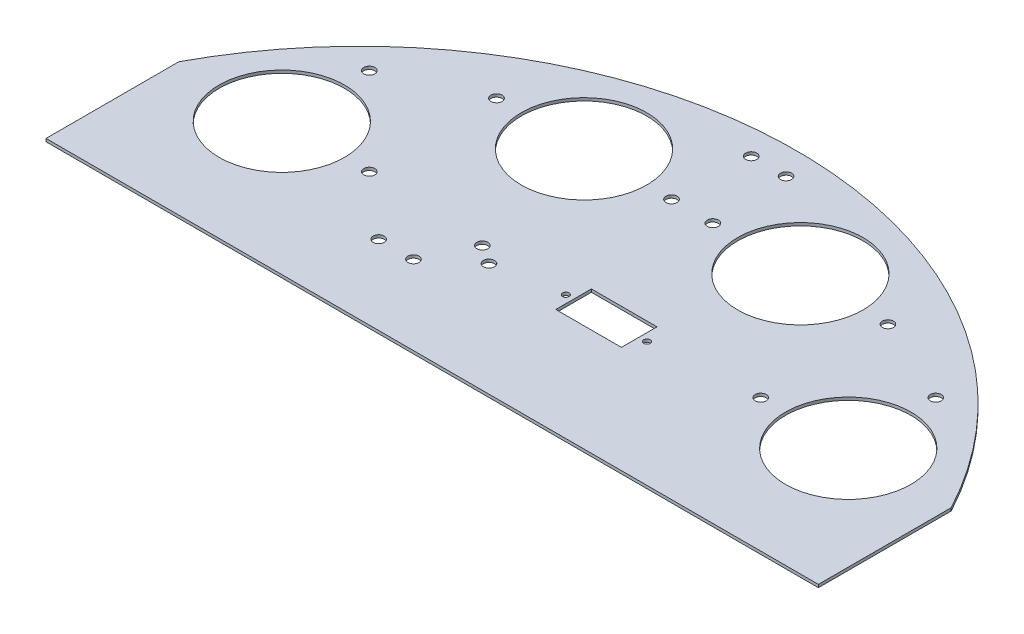
SolidWorks part; units mm, degrees
material "1060 Alloy"
ref_plane "Front Plane" through (0, 0, 0) normal (0, 0, 1) x (1, 0, 0)
ref_plane "Top Plane" through (0, 0, 0) normal (0, 1, 0) x (1, 0, 0)
ref_plane "Right Plane" through (0, 0, 0) normal (1, 0, 0) x (0, 0, -1)
sketch "Sketch3" plane through (0, 0, 0) normal (0, 1, 0) x (1, 0, 0)
  line L5 (-149.8445, -43.9726) -> (150.1555, -43.9726) construction
  line L6 (97.2375, 26.5616) -> (0.1555, -43.9726)
  line L7 (-86.3026, -18.9726) -> (-147.7465, -18.9726)
  line L8 (-132.2262, 26.5616) -> (-132.2262, -18.9726)
  line L9 (86.6136, -18.9726) -> (148.0575, -18.9726)
  line L10 (132.5372, 26.5616) -> (132.5372, -18.9726)
  line L11 (86.6136, -18.9726) -> (-86.3026, -18.9726)
  circle A10 centre (0.1555, -43.9726) radius 120 construction
  circle A11 centre (0.1555, -43.9726) radius 90 construction
  circle A12 centre (0.1555, -43.9726) radius 150
  circle A13 centre (97.2375, 26.5616) radius 21.5
  circle A14 centre (37.2375, 70.1542) radius 21.5
  circle A15 centre (-36.9265, 70.1542) radius 21.5
  circle A16 centre (-96.9265, 26.5616) radius 21.5
  point P5 (0.1555, -43.9726)
  point P9 (0.1555, -43.9726)
  point P22 (0.1555, -43.9726)
  dimension "D3" = 300
  dimension "D7" = 43
  dimension "D4" = 36
  dimension "D5" = 4
  dimension "D2" = 240
  dimension "D1" = 180
  dimension "D6" = 25
extrude "Boss-Extrude3" add sketch "Sketch3" along normal blind 1
sketch "Sketch5" plane through (0, 1, 0) normal (0, 1, 0) x (1, 0, 0)
  line L0 (37.2375, 70.1542) -> (-36.9265, 70.1542) construction
  line L1 (-36.9265, 70.1542) -> (-96.9265, 26.5616) construction
  line L2 (37.2375, 70.1542) -> (97.2375, 26.5616) construction
  circle A0 centre (97.2375, 26.5616) radius 30 construction
  circle A1 centre (37.2375, 70.1542) radius 30 construction
  circle A2 centre (-36.9265, 70.1542) radius 30 construction
  circle A3 centre (-96.9265, 26.5616) radius 30 construction
  point P12 (67.2375, 26.5616)
  point P13 (97.2375, 56.5616)
  point P14 (7.2375, 70.1542)
  point P15 (67.2375, 70.1542)
  point P16 (-6.9265, 70.1542)
  point P17 (-66.9265, 70.1542)
  point P18 (-96.9265, 56.5616)
  point P19 (-66.9265, 26.5616)
sketch "Sketch10" plane through (0, 0, 0) normal (0, -1, 0) x (-1, 0, 0)
  line L0 (-28.4264, 17.6232) -> (-16.5209, 17.6232)
  line L1 (-27.5764, 17.6232) -> (-6.7764, 17.6232) construction
  line L2 (-28.4264, 17.6232) -> (-28.4264, 29.8232)
  line L3 (-28.4264, 29.8232) -> (-5.9264, 29.8232)
  line L4 (-5.9264, 29.8232) -> (-5.9264, 17.6232)
  line L5 (-5.9264, 17.6232) -> (-28.4264, 17.6232)
  line L6 (-5.9264, 18.4732) -> (-5.9264, 28.9732) construction
  line L7 (-6.7764, 29.8232) -> (-27.5764, 29.8232) construction
  line L8 (-28.4264, 28.9732) -> (-28.4264, 18.4732) construction
  line L9 (43.9148, 8.1232) -> (26.8038, 8.1232) construction
  line L10 (4.3576, 96.6113) -> (-7.7151, 96.6113) construction
  line L11 (-0.0313, 92.8613) -> (-0.0264, 100.3613) construction
  line L12 (39.2014, 4.3732) -> (39.2014, 11.8732) construction
  line L13 (32.1421, 28.2546) -> (19.1543, 19.7949) construction
  line L14 (28.105, 20.253) -> (21.0773, 31.0423) construction
  circle A0 centre (-0.0264, 100.3613) radius 2.5 construction
  circle A1 centre (-0.0313, 92.8613) radius 2.5 construction
  circle A2 centre (39.2014, 4.3732) radius 2.5 construction
  circle A3 centre (39.2014, 11.8732) radius 2.5 construction
  circle A4 centre (19.1543, 19.7949) radius 2.5 construction
  circle A5 centre (32.1421, 28.2546) radius 2.5 construction
  circle A6 centre (-31.0764, 23.7232) radius 1.1
  circle A7 centre (-3.2764, 23.7232) radius 1.1
  dimension "D1" = 3.75
  dimension "D2" = 3.75
  dimension "D3" = 7.75
extrude "Cut-Extrude3" cut sketch "Sketch10" against normal through all contours L5 L4 L3 L2 L0 | A5 | A4 | A3 | A2 | A1 | A0 | A6 | A7
hole_wizard "#6 Clearance Hole1" positions "Sketch8" profile "Sketch9" hole size "#6" standard "ANSI Inch" end condition through all
sketch "Sketch8" plane through (0, 0, 0) normal (0, -1, 0) x (-1, 0, 0)
  line L0 (43.9148, 8.1232) -> (26.8038, 8.1232) construction
  line L1 (39.2014, 4.3732) -> (39.2014, 11.8732) construction
  line L2 (4.3576, 96.6113) -> (-7.7151, 96.6113) construction
  line L3 (-0.0313, 92.8613) -> (-0.0264, 100.3613) construction
  line L4 (32.1421, 28.2546) -> (19.1543, 19.7949) construction
  point P0 (-97.2375, 56.5616)
  point P2 (-67.2375, 26.5616)
  point P4 (-67.2375, 70.1542)
  point P6 (-7.2375, 70.1542)
  point P8 (6.9265, 70.1542)
  point P10 (66.9265, 70.1542)
  point P12 (96.9265, 56.5616)
  point P14 (66.9265, 26.5616)
  point P50 (19.1543, 19.7949)
  point P53 (45.2914, 8.1232)
  point P55 (33.3614, 8.1232)
  point P75 (6.0611, 96.6113)
  point P79 (-5.8689, 96.6113)
  point P84 (25.6482, 24.0247)
  dimension "D1" = 6.09
  dimension "D2" = 5.84
  dimension "D3" = 6.09
  dimension "D4" = 5.84
sketch "Sketch9" plane through (97.2375, 0, -56.5616) normal (1, 0, 0) x (0, 0, -1)
  line L0 (0, 0) -> (0, 1)
  line L1 (0, 1) -> (1.8986, 1)
  line L2 (1.8986, 1) -> (1.8986, 0)
  line L5 (1.8986, 0) -> (0, 0)
  line L11 (0, -6.35) -> (0, 107.95) construction
  dimension "Thru Hole Dia." = 3.7973
  dimension "Thru Hole Depth" = 1
